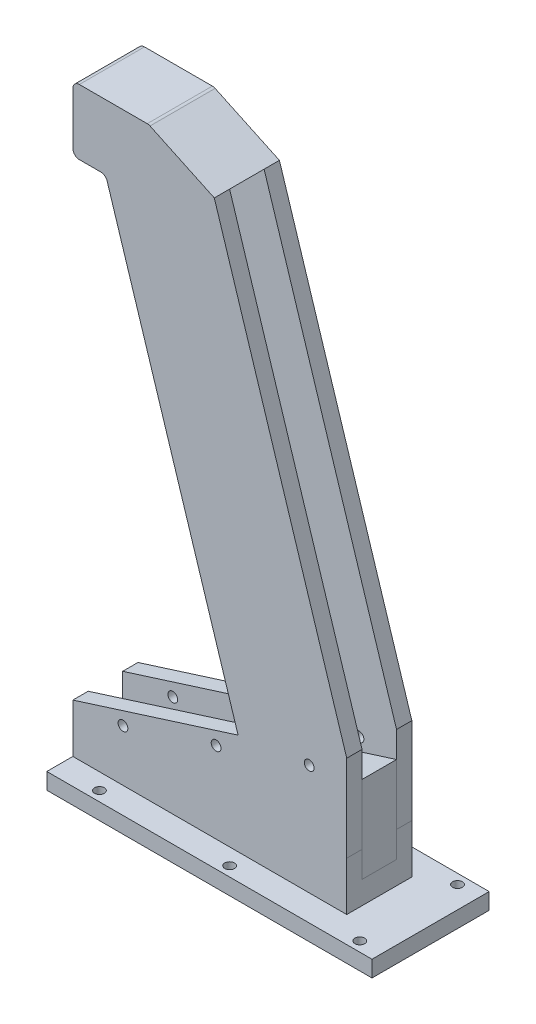
SolidWorks part; units mm, degrees
ref_plane "Front Plane" through (0, 0, 0) normal (0, 0, 1) x (1, 0, 0)
ref_plane "Top Plane" through (0, 0, 0) normal (0, 1, 0) x (1, 0, 0)
ref_plane "Right Plane" through (0, 0, 0) normal (1, 0, 0) x (0, 0, -1)
sketch "Sketch1" plane through (0, 0, 0) normal (0, 1, 0) x (1, 0, 0)
  line L0 (-42.8539, -10) -> (41.2839, -10)
  line L1 (-42.8539, -10) -> (-42.8539, 10)
  line L2 (-42.8539, 10) -> (41.2839, 10)
  line L3 (41.2839, -10) -> (41.2839, 10)
  line L4 (-42.8539, -10) -> (41.2839, 10) construction
  line L5 (-42.8539, 10) -> (41.2839, -10) construction
  point P0 (-0.785, 0)
  point P1 (-0.785, 0)
  point P6 (-0.785, 0)
  dimension "D1" = 20
  dimension "D2" = 84.1377
extrude "Boss-Extrude1" add sketch "Sketch1" along normal blind 15
sketch "Sketch5" plane through (-42.8539, 0, 0) normal (-1, 0, 0) x (0, 0, 1)
  line L8 (-10, 15) -> (-5.3, 15) construction
  line L10 (-10, 15) -> (10, 15) construction
  line L11 (10, 15) -> (5.3, 15) construction
  line L12 (-5.3, 15) -> (-5.3, 7)
  line L13 (5.3, 15) -> (5.3, 7)
  line L14 (-5.3, 7) -> (5.3, 7)
  line L15 (-5.3, 15) -> (5.3, 15)
  dimension "D1" = 4.7
  dimension "D2" = 4.7
  dimension "D3" = 8
  dimension "D4" = 8
extrude "Cut-Extrude1" cut sketch "Sketch5" against normal blind 85.71
sketch "Sketch8" plane through (0, 0, 0) normal (0, -1, 0) x (1, 0, 0)
  line L0 (-52.8539, 18) -> (57.0439, 18)
  line L5 (57.0439, -18) -> (57.0439, 18)
  line L6 (-52.8539, -18) -> (57.0439, -18)
  line L7 (-52.8539, -18) -> (-52.8539, 18)
  line L8 (41.2839, 10) -> (41.2839, -10) construction
  line L11 (41.2839, -10) -> (-42.8539, -10)
  line L12 (-42.8539, 10) -> (-42.8539, -10)
  line L13 (-42.8539, -10) -> (41.2839, -10)
  line L14 (-42.8539, -10) -> (-42.8539, 10)
  line L15 (-42.8539, 10) -> (41.2839, 10)
  line L16 (41.2839, -10) -> (41.2839, 10)
  line L17 (-42.8539, 10) -> (41.2839, 10) construction
  line M3 (-42.8539, -10) -> (41.2839, -10)
  line M5 (41.2839, 10) -> (-42.8539, 10)
  line M6 (-42.8539, 10) -> (-42.8539, -10)
  line M13 (41.2839, -10) -> (41.2839, 10)
  dimension "D1" = 8
  dimension "D2" = 109.8977
  dimension "D3" = 15.76
  dimension "D4" = 28
extrude "Boss-Extrude4" add sketch "Sketch8" along normal blind 5 separate body contours L7 L6 L5 L0 M13 M3 M6 M5 | M3 M13 M5 M6
sketch "Sketch9" plane through (0, 0, 0) normal (0, 1, 0) x (1, 0, 0)
  line L0 (-52.8539, -18) -> (-42.8539, -18)
  line L5 (-62.3378, 0) -> (61.6471, 0) construction
  line L6 (-42.8539, -18) -> (-42.8539, 18)
  line L7 (-52.8539, 18) -> (-52.8539, -18) construction
  line L11 (-52.8539, 18) -> (-52.8539, -18) construction
  line L13 (-52.8539, -18) -> (57.0439, -18) construction
  line L15 (-52.8539, 18) -> (57.0439, 18) construction
  circle A6 centre (-29.6939, 15) radius 1.5
  circle A7 centre (10.3061, 15) radius 1.5
  circle A8 centre (50.3061, 15) radius 1.5
  circle A9 centre (10.3061, -15) radius 1.5
  circle A10 centre (50.3061, -15) radius 1.5
  circle A11 centre (-29.6939, -15) radius 1.5
  line M33 (-52.8539, 18) -> (-52.8539, -18)
  line M34 (-52.8539, -18) -> (57.0439, -18)
  line M36 (57.0439, 18) -> (-52.8539, 18)
  dimension "D1" = 23.16
  dimension "D4" = 3
  dimension "D5" = 3
  dimension "D2" = 3
  dimension "D3" = 2
  dimension "D6" = 10
  dimension "D7" = 63.16
  dimension "D8" = 3
  dimension "D9" = 36
extrude "Cut-Extrude3" cut sketch "Sketch9" against normal through all contours A6 | A7 | A11 | A10 | A8 | L5 L6 M33 M36 | L5 L6 M33 M34 | A9
sketch "Sketch11" plane through (0, 0, -5.3) normal (0, 0, 1) x (1, 0, 0)
  line L0 (-42.8539, 7) -> (41.2836, 33.593)
  line L1 (-42.8539, 7) -> (41.2836, 7)
  line L2 (-42.8539, 7) -> (-42.8539, 15)
  line L3 (41.2836, 33.593) -> (41.2836, 41.593)
  line L4 (-42.8539, 15) -> (41.2836, 41.593)
  line L5 (41.2836, 7) -> (41.2836, 33.593)
  line L6 (-42.8539, 7) -> (41.2836, 7)
  line M5 (41.2839, 15) -> (-42.8539, 15)
  line M7 (-42.8539, 7) -> (41.2839, 7)
  dimension "D1" = 88.24
  dimension "D2" = 8
extrude "Boss-Extrude7" add sketch "Sketch11" along normal up to surface (10.6 mm away) contours L5 L0 M5 | L5 L0 M7 M5 up to face at (-0.785, 11, 5.3)
sketch "Sketch13" plane through (0, 0, -5.3) normal (0, 0, 1) x (1, 0, 0)
  line L0 (-42.8539, 7) -> (-42.8539, 15)
  line L1 (-42.8539, 15) -> (41.2836, 41.593)
  line L4 (-42.8539, 15) -> (41.2839, 15) construction
  line L5 (41.2836, 41.593) -> (41.2836, 33.593)
  line L6 (41.2836, 33.593) -> (-42.8539, 7)
  line L7 (-17.5427, 15) -> (41.2836, 15)
  line L8 (41.2836, 15) -> (41.2836, 33.593)
  line M6 (41.2839, 15) -> (-42.8539, 15)
  dimension "D1" = 17.54
  dimension "D2" = 88.24
extrude "Boss-Extrude8" add sketch "Sketch13" against normal blind 4.7 contours L6 L5 L1 M6 | L7 L8 L6
sketch "Sketch14" plane through (0, 0, 5.3) normal (0, 0, -1) x (-1, 0, 0)
  line L0 (42.8539, 15) -> (-41.2836, 41.593)
  line L1 (-41.2836, 41.593) -> (-41.2836, 15)
  line L2 (-41.2836, 15) -> (42.8539, 15)
extrude "Boss-Extrude9" add sketch "Sketch14" against normal blind 4.7
sketch "Sketch15" plane through (0, 0, -5.3) normal (0, 0, 1) x (1, 0, 0)
  line L0 (-42.8539, 7) -> (41.2836, 33.593) construction
  line L1 (-42.8539, 15) -> (-40.555, 7.7266) construction
  line L2 (-41.7044, 11.3633) -> (44.8654, 38.7251) construction
  circle A0 centre (-27.459, 15.8658) radius 1.5
  circle A1 centre (1.1462, 24.9069) radius 1.5
  circle A2 centre (29.7514, 33.9481) radius 1.5
  dimension "D1" = 3
  dimension "D2" = 14.94
  dimension "D3" = 3
extrude "Cut-Extrude4" cut sketch "Sketch15" against normal through all both and the other way through all
sketch "Sketch26" plane through (-8.2026, 25.9521, 0) normal (-0.3014, 0.9535, 0) x (0.9535, 0.3014, 0)
  line L0 (51.8991, 10) -> (16.8991, 10)
  line L1 (-36.3409, 10) -> (51.8991, 10) construction
  line L2 (16.8991, 10) -> (16.8991, 5.3)
  line L4 (16.8991, 5.3) -> (51.8991, 5.3)
  line L5 (-36.3409, 5.3) -> (51.8991, 5.3) construction
  line L6 (51.8991, 5.3) -> (51.8991, 10)
ref_plane "Plane3" through (-8.2026, 25.9521, 0) normal (-0.3014, 0.9535, 0) x (0.9535, 0.3014, 0)
sketch "Sketch28" plane through (-8.2026, 25.9521, 0) normal (-0.3014, 0.9535, 0) x (0.9535, 0.3014, 0)
  line L0 (51.8991, 10) -> (16.8991, 10)
  line L1 (16.8991, 10) -> (16.8991, 5.3)
  line L2 (16.8991, 5.3) -> (51.8991, 5.3)
  line L3 (51.8991, 5.3) -> (51.8991, 10)
  line L4 (51.8991, 10) -> (51.8991, -10) construction
  line L5 (52.8466, 0) -> (13.4842, 0) construction
  line L6 (-36.3409, -5.3) -> (51.8991, -5.3) construction
  line L7 (51.8991, -10) -> (16.8991, -10)
  line L8 (51.8991, -10) -> (51.8991, -5.3)
  line L9 (51.8991, -5.3) -> (16.8991, -5.3)
  line L10 (16.8991, -10) -> (16.8991, -5.3)
  dimension "D1" = 35
  dimension "D2" = 4.7
extrude "Boss-Extrude11" add sketch "Sketch28" along normal blind 135
ref_plane "Plane4" through (0, 0, 0) normal (0, 0, 1) x (1, 0, 0)
ref_plane "Plane5" through (-42.8539, 0, 0) normal (-1, 0, 0) x (0, 0, 1)
sketch "Sketch31" plane through (0, 0, -10) normal (0, 0, -1) x (-1, 0, 0)
  line L4 (42.8534, 179.7684) -> (42.8534, 159.7684)
  line L5 (42.8534, 159.7684) -> (32.7743, 159.7684)
  line L6 (32.7743, 159.7684) -> (-0.5984, 170.3164)
  line L7 (-0.5984, 170.3164) -> (19.5534, 179.7684)
  line L8 (19.5534, 179.7684) -> (42.8534, 179.7684)
  dimension "D1" = 20
  dimension "D2" = 23.3
  dimension "D3" = 20.1518
extrude "Boss-Extrude15" add sketch "Sketch31" against normal blind 20
fillet "Fillet2" radius 2 5 edges at (-32.7743, 159.7684, 7.65) (-32.7743, 159.7684, -7.65) (-42.8534, 159.7684, 0) (-42.8534, 179.7684, 0) (-19.5534, 179.7684, 0)
